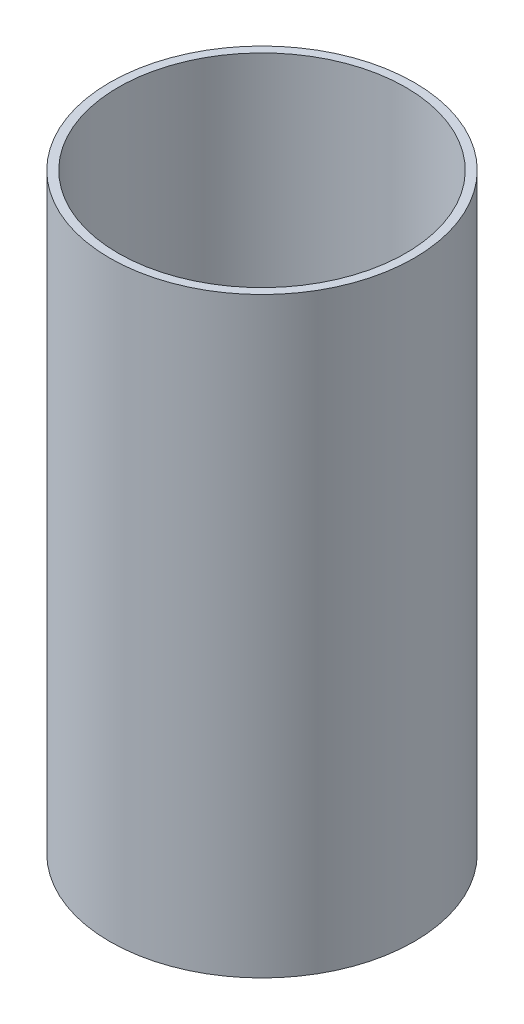
SolidWorks part; units mm, degrees
ref_plane "Front Plane" through (0, 0, 0) normal (0, 0, 1) x (1, 0, 0)
ref_plane "Top Plane" through (0, 0, 0) normal (0, 1, 0) x (1, 0, 0)
ref_plane "Right Plane" through (0, 0, 0) normal (1, 0, 0) x (0, 0, -1)
sketch "Sketch1" plane through (0, 0, 0) normal (0, 1, 0) x (1, 0, 0)
  circle A0 centre (0, 0) radius 27
  circle A1 centre (0, 0) radius 25.5
  dimension "D1" = 54
  dimension "D2" = 1.5
extrude "Boss-Extrude1" add sketch "Sketch1" along normal blind 105
